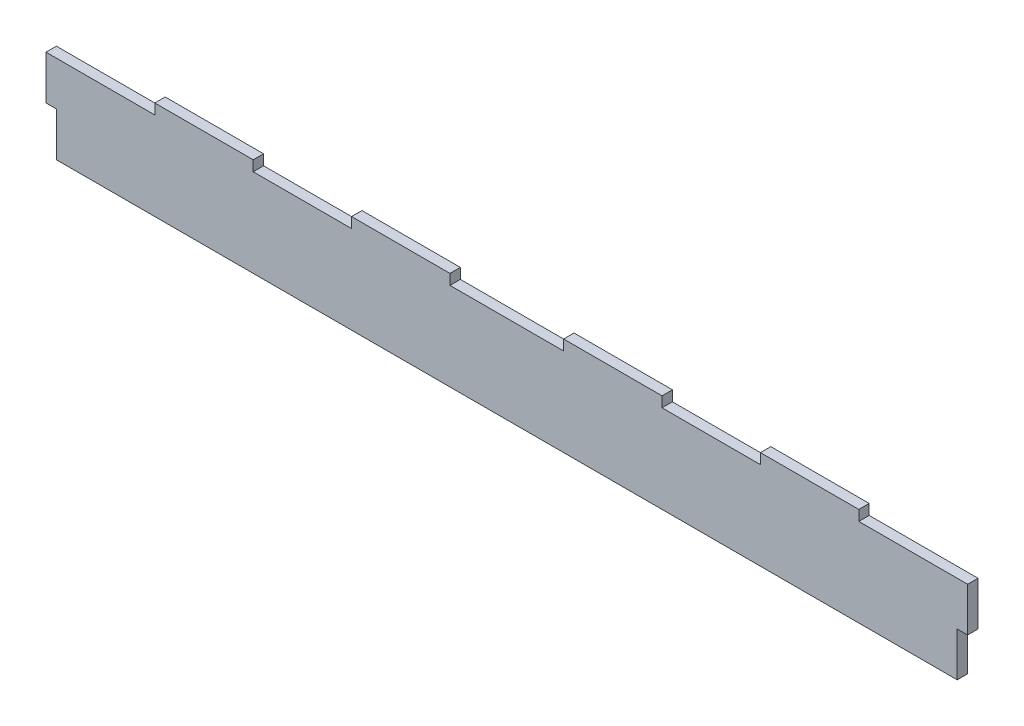
SolidWorks part; units mm, degrees
ref_plane "Alzado" through (0, 0, 0) normal (0, 0, 1) x (1, 0, 0)
ref_plane "Planta" through (0, 0, 0) normal (0, 1, 0) x (1, 0, 0)
ref_plane "Vista lateral" through (0, 0, 0) normal (1, 0, 0) x (0, 0, -1)
sketch "Croquis1" plane through (0, 0, 0) normal (0, 0, 1) x (1, 0, 0)
  line L0 (0, 25.4) -> (0, 12.7)
  line L1 (0, 25.4) -> (3, 25.4)
  line L2 (3, 25.4) -> (31.4, 25.4)
  line L3 (31.4, 25.4) -> (31.4, 28.4)
  line L4 (31.4, 28.4) -> (59.8, 28.4)
  line L5 (59.8, 28.4) -> (59.8, 25.4)
  line L6 (59.8, 25.4) -> (88.2, 25.4)
  line L7 (88.2, 25.4) -> (88.2, 28.4)
  line L8 (88.2, 28.4) -> (116.6, 28.4)
  line L9 (116.6, 28.4) -> (116.6, 25.4)
  line L10 (0, 12.7) -> (3, 12.7)
  line L11 (3, 12.7) -> (3, 0)
  line L12 (0, 0) -> (266, 0) construction
  line L13 (133, 0) -> (133, 33.8732) construction
  line L14 (263, 12.7) -> (263, 0)
  line L15 (266, 12.7) -> (263, 12.7)
  line L16 (149.4, 28.4) -> (149.4, 25.4)
  line L17 (177.8, 28.4) -> (149.4, 28.4)
  line L18 (177.8, 25.4) -> (177.8, 28.4)
  line L19 (206.2, 25.4) -> (177.8, 25.4)
  line L20 (206.2, 28.4) -> (206.2, 25.4)
  line L21 (234.6, 28.4) -> (206.2, 28.4)
  line L22 (234.6, 25.4) -> (234.6, 28.4)
  line L23 (263, 25.4) -> (234.6, 25.4)
  line L24 (266, 25.4) -> (263, 25.4)
  line L25 (266, 25.4) -> (266, 12.7)
  line L26 (116.6, 25.4) -> (149.4, 25.4)
  line L27 (3, 0) -> (263, 0)
  point P31 (266, 19.05)
  dimension "D1" = 3
  dimension "D2" = 12.7
  dimension "D3" = 12.7
  dimension "D4" = 28.4
  dimension "D5" = 3
  dimension "D6" = 266
  dimension "D7" = 3
extrude "Saliente-Extruir1" add sketch "Croquis1" along normal blind 3
